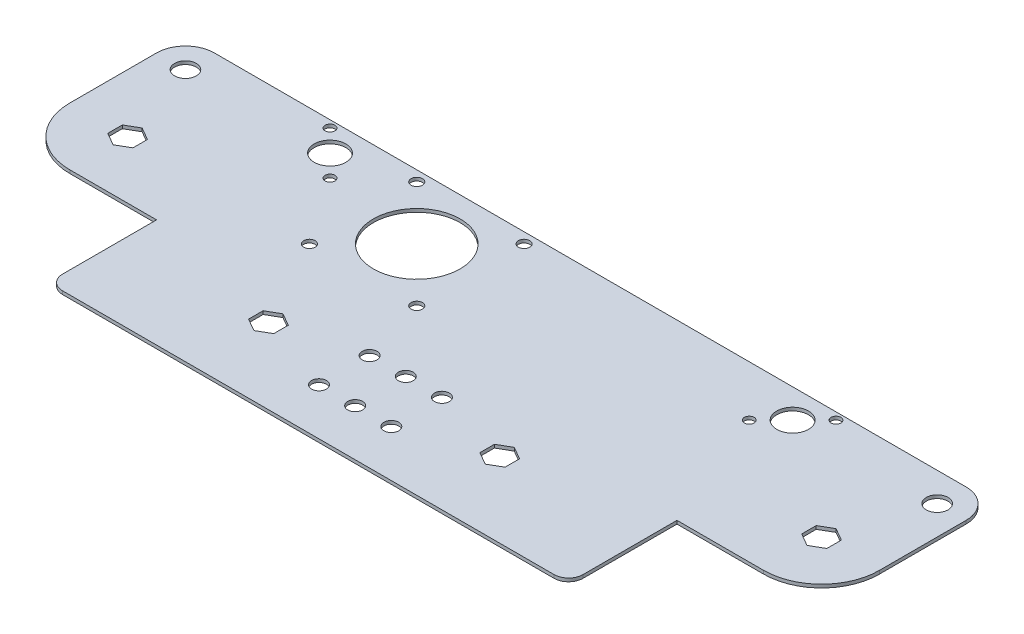
SolidWorks part; units mm, degrees
ref_plane "Front Plane" through (0, 0, 0) normal (0, 0, 1) x (1, 0, 0)
ref_plane "Top Plane" through (0, 0, 0) normal (0, 1, 0) x (1, 0, 0)
ref_plane "Right Plane" through (0, 0, 0) normal (1, 0, 0) x (0, 0, -1)
sketch "Sketch1" plane through (0, 0, 0) normal (0, 1, 0) x (1, 0, 0)
  line L0 (-4.4545, -219.7672) -> (-4.4545, -257.8672) construction
  line L1 (-70.7485, -286.8232) -> (-108.8485, -286.8232)
  line L2 (-70.7485, -286.8232) -> (-70.7485, -328.0982)
  line L3 (-64.3985, -334.4482) -> (151.5015, -334.4482)
  line L4 (14.5955, -238.8172) -> (-23.5045, -238.8172) construction
  line L5 (-134.2485, -261.4232) -> (-134.2485, -223.3232)
  line L6 (-121.5485, -210.6232) -> (208.6515, -210.6232)
  line L7 (221.3515, -223.3232) -> (221.3515, -261.4232)
  line L8 (195.9515, -286.8232) -> (157.8515, -286.8232)
  line L20 (43.5515, -334.4482) -> (43.5515, 211.8848) construction
  line L21 (-1.724, -304.3638) -> (-1.724, -297.9846)
  line L22 (-1.724, -297.9846) -> (-7.2485, -294.7951)
  line L23 (-7.2485, -294.7951) -> (-12.773, -297.9846)
  line L24 (-12.773, -297.9846) -> (-12.773, -304.3638)
  line L25 (-12.773, -304.3638) -> (-7.2485, -307.5533)
  line L26 (-7.2485, -307.5533) -> (-1.724, -304.3638)
  line L27 (157.8515, -286.8232) -> (157.8515, -328.0982)
  line L28 (94.3515, -307.5533) -> (88.827, -304.3638)
  line L29 (99.876, -304.3638) -> (94.3515, -307.5533)
  line L30 (99.876, -297.9846) -> (99.876, -304.3638)
  line L31 (94.3515, -294.7951) -> (99.876, -297.9846)
  line L32 (88.827, -297.9846) -> (94.3515, -294.7951)
  line L33 (88.827, -304.3638) -> (88.827, -297.9846)
  line L34 (-32.6485, -210.6232) -> (-32.6485, -242.8626) construction
  line L35 (-103.324, -258.2336) -> (-108.8485, -255.0441)
  line L36 (-108.8485, -255.0441) -> (-114.373, -258.2336)
  line L37 (-114.373, -258.2336) -> (-114.373, -264.6128)
  line L38 (-114.373, -264.6128) -> (-108.8485, -267.8023)
  line L39 (-108.8485, -267.8023) -> (-103.324, -264.6128)
  line L40 (-103.324, -264.6128) -> (-103.324, -258.2336)
  line L41 (201.476, -264.6128) -> (195.9515, -267.8023)
  line L42 (201.476, -258.2336) -> (201.476, -264.6128)
  line L43 (195.9515, -255.0441) -> (201.476, -258.2336)
  line L44 (190.427, -258.2336) -> (195.9515, -255.0441)
  line L45 (195.9515, -267.8023) -> (190.427, -264.6128)
  line L46 (190.427, -264.6128) -> (190.427, -258.2336)
  circle A0 centre (27.6765, -291.6492) radius 3.2639
  circle A1 centre (43.5515, -291.6492) radius 3.2639
  circle A2 centre (59.4265, -291.6492) radius 3.2639
  circle A3 centre (-28.0257, -215.246) radius 2.5019
  circle A4 centre (-28.0257, -262.3884) radius 2.5019
  circle A5 centre (19.1167, -215.246) radius 2.5019
  circle A6 centre (19.1167, -262.3884) radius 2.5019
  circle A8 centre (-7.2485, -301.1742) radius 5.5245 construction
  circle A9 centre (94.3515, -301.1742) radius 5.5245 construction
  arc A10 (-108.8485, -286.8232) -> (-134.2485, -261.4232) centre (-108.8485, -261.4232) cw
  arc A11 (221.3515, -261.4232) -> (195.9515, -286.8232) centre (195.9515, -261.4232) cw
  circle A12 centre (27.6765, -313.8742) radius 3.2639
  circle A13 centre (43.5515, -313.8742) radius 3.2639
  circle A14 centre (59.4265, -313.8742) radius 3.2639
  circle A15 centre (-108.8485, -261.4232) radius 5.5245 construction
  circle A16 centre (-58.0485, -223.3232) radius 6.985
  circle A17 centre (-67.5735, -213.7982) radius 2.159
  circle A18 centre (-48.5235, -232.8482) radius 2.159
  circle A19 centre (-4.4545, -238.8172) radius 19.05
  circle A20 centre (135.6265, -232.8482) radius 2.159
  circle A21 centre (145.1515, -223.3232) radius 6.985
  circle A22 centre (154.6765, -213.7982) radius 2.159
  circle A23 centre (195.9515, -261.4232) radius 5.5245 construction
  arc A24 (208.6515, -210.6232) -> (221.3515, -223.3232) centre (208.6515, -223.3232) cw
  arc A25 (-134.2485, -223.3232) -> (-121.5485, -210.6232) centre (-121.5485, -223.3232) cw
  arc A26 (151.5015, -334.4482) -> (157.8515, -328.0982) centre (151.5015, -328.0982) ccw
  arc A27 (-70.7485, -328.0982) -> (-64.3985, -334.4482) centre (-64.3985, -328.0982) ccw
  circle A28 centre (-121.5485, -223.3232) radius 4.7625
  circle A30 centre (208.6515, -223.3232) radius 4.7625
  point P61 (-134.2485, -286.8232)
  point P105 (-134.2485, -210.6232)
  point P110 (-70.7485, -334.4482)
  dimension "D11" = 47.1424
  dimension "D12" = 22.225
  dimension "D17" = 63.5
  dimension "D18" = 25.4
  dimension "D14" = 25.4
  dimension "D15" = 12.7
  dimension "D19" = 6.5278
  dimension "D21" = 6.5278
  dimension "D22" = 6.5278
  dimension "D23" = 15.875
  dimension "D24" = 15.875
  dimension "D25" = 12.7
  dimension "D28" = 13.97
  dimension "D30" = 4.318
  dimension "D31" = 4.318
  dimension "D32" = 9.525
  dimension "D33" = 9.525
  dimension "D34" = 9.525
  dimension "D35" = 9.525
  dimension "D36" = 25.4
  dimension "D38" = 38.1
  dimension "D40" = 6.35
  dimension "D41" = 9.525
  dimension "D42" = 9.525
  dimension "D6" = 2
  dimension "D7" = 5.0038
  dimension "D9" = 47.1424
  dimension "D2" = 47.625
  dimension "D5" = 33.274
  dimension "D8" = 11.049
  dimension "D10" = 101.6
  dimension "D16" = 25.4
  dimension "D20" = 76.2
  dimension "D26" = 11.049
  dimension "D27" = 12.7
  dimension "D29" = 101.6
  dimension "D37" = 28.194
  dimension "D39" = 28.194
  dimension "D43" = 355.6
extrude "Boss-Extrude1" add sketch "Sketch1" along normal blind 1.4478
